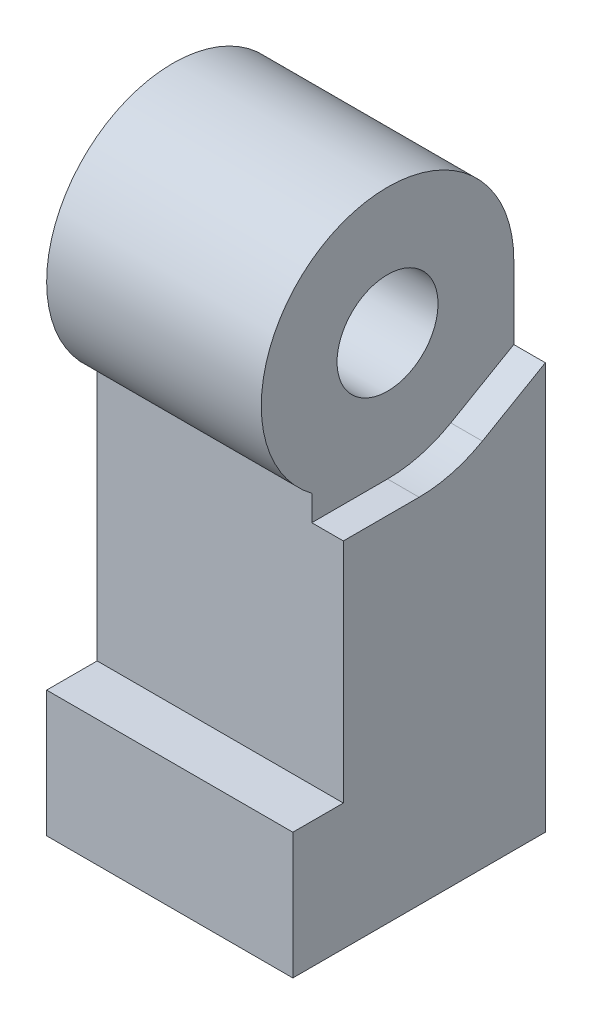
SolidWorks part; units mm, degrees
material "ABS"
ref_plane "Front Plane" through (0, 0, 0) normal (0, 0, 1) x (1, 0, 0)
ref_plane "Top Plane" through (0, 0, 0) normal (0, 1, 0) x (1, 0, 0)
ref_plane "Right Plane" through (0, 0, 0) normal (1, 0, 0) x (0, 0, -1)
sketch "Sketch1" plane through (0, 0, 0) normal (0, 1, 0) x (1, 0, 0)
  line L1 (0, -10) -> (10, -10)
  line L2 (0, -10) -> (0, 0)
  line L3 (0, 0) -> (10, 0)
  line L4 (10, -10) -> (10, 0)
  dimension "D1" = 10
  dimension "D2" = 10
extrude "Foot" add sketch "Sketch1" along normal blind 5
sketch "Sketch2" plane through (0, 5, 0) normal (0, 1, 0) x (1, 0, 0)
  line L0 (10, -10) -> (10, 0) construction
  line L1 (0, 0) -> (10, 0)
  line L2 (0, 0) -> (0, -8)
  line L3 (0, -8) -> (10, -8)
  line L4 (10, 0) -> (10, -8)
  line L5 (0, -10) -> (10, -10) construction
  dimension "D1" = 2
  dimension "D2" = 10
extrude "Leg" add sketch "Sketch2" along normal blind 14
sketch "Sketch3" plane through (0, 0, 0) normal (1, 0, 0) x (0, 0, -1)
  line L0 (0, 19) -> (-8, 19) construction
  circle A0 centre (-5, 19) radius 5
  dimension "D1" = 10
  dimension "D2" = 5
extrude "Hip Connector" add sketch "Sketch3" against normal up to surface (10 mm away)
sketch "Sketch20" plane through (0, 0, 0) normal (-1, 0, 0) x (0, 0, 1)
  circle A0 centre (5, 19) radius 3.5
  dimension "D1" = 7
extrude "Decorative circle that makes this easy to dimension" cut sketch "Sketch20" against normal blind 0.1
sketch "Sketch4" plane through (10, 0, 0) normal (1, 0, 0) x (0, 0, -1)
  line L0 (-5, 13.99) -> (-10, 13.99)
  line L1 (0, 19) -> (-10, 19) construction
  line L2 (-10, 13.99) -> (-10, 24)
  line L3 (-10, 24) -> (0, 24)
  line L4 (-2.495, 14.6612) -> (0, 16.1017)
  line L5 (0, 16.1017) -> (0, 24)
  line L6 (-5, 19) -> (-5, 13.99) construction
  line L7 (-5, 19) -> (-2.495, 14.6612) construction
  arc A1 (-5, 13.99) -> (-2.495, 14.6612) centre (-5, 19) ccw
  arc A2 (0, 19) -> (-8, 15) centre (-5, 19) ccw construction
  dimension "D1" = 30
  dimension "D2" = 10
  dimension "D3" = 5.01
  dimension "D4" = 10.01
extrude "Hip room" cut sketch "Sketch4" against normal blind 1.5
hole_wizard "Hip hole" positions "Sketch16" profile "Sketch17" hole size "Ø4.0" standard "ANSI Metric"
sketch "Sketch16" plane through (8.5, 0, 0) normal (1, 0, 0) x (0, 0, -1)
  point P11 (-5, 19)
sketch "Sketch17" plane through (8.5, 19, 5) normal (0, 1, 0) x (0, 0, -1)
  line L0 (0, 0) -> (0, 7.2017)
  line L1 (0, 7.2017) -> (2, 6)
  line L2 (2, 6) -> (2, 0)
  line L5 (2, 0) -> (0, 0)
  line L10 (0, 7.2017) -> (-2, 6) construction
  line L11 (0, -6.35) -> (0, 107.95) construction
  dimension "Hole Dia." = 4
  dimension "Hole Depth" = 6
  dimension "Drill Angle" = 118
sketch "Sketch18" plane through (0, 0, 0) normal (0, -1, 0) x (1, 0, 0)
  line L0 (0, 0) -> (0, 10) construction
  line L1 (2, 2) -> (8, 2)
  line L2 (2, 2) -> (2, 8)
  line L3 (2, 8) -> (8, 8)
  line L4 (8, 2) -> (8, 8)
  line L7 (0, 10) -> (10, 10) construction
  line L8 (10, 0) -> (0, 0) construction
  dimension "D1" = 2
  dimension "D4" = 2
  dimension "D3" = 2
  dimension "D2" = 6
extrude "Foot hole" cut sketch "Sketch18" against normal blind 2.5
hole_wizard "Weight reduction/make it easy to add centerline hole" positions "Sketch24" profile "Sketch23" hole size "Ø3.0" standard "ANSI Metric"
sketch "Sketch24" plane through (0, 2.5, 0) normal (0, -1, 0) x (-1, 0, 0)
  point P0 (-5, -5)
sketch "Sketch23" plane through (5, 2.5, 5) normal (1, 0, 0) x (0, 0, -1)
  line L0 (0, 0) -> (0, 8.9013)
  line L1 (0, 8.9013) -> (1.5, 8)
  line L2 (1.5, 8) -> (1.5, 0)
  line L5 (1.5, 0) -> (0, 0)
  line L10 (0, 8.9013) -> (-1.5, 8) construction
  line L11 (0, -6.35) -> (0, 107.95) construction
  dimension "Hole Dia." = 3
  dimension "Hole Depth" = 8
  dimension "Drill Angle" = 118
sketch "Sketch19" plane through (10, 0, 0) normal (1, 0, 0) x (0, 0, -1)
  line L1 (-10, 0) -> (0, 0)
  line L2 (-10, 0) -> (-10, 20)
  line L3 (-10, 20) -> (0, 20)
  line L4 (0, 0) -> (0, 20)
  dimension "D1" = 20
extrude "Thigh gap" cut sketch "Sketch19" against normal blind 0.25
fillet "Smoothing edges" [suppressed] radius 0.1
scale "Scale1" scale about centroid uniform scaling yes scale factor 2
equation "\"D4@Sketch18\"=\"D1@Sketch18\""
equation "\"D2@Sketch18\"=6"
equation "\"D3@Sketch18\"=\"D1@Sketch18\""
